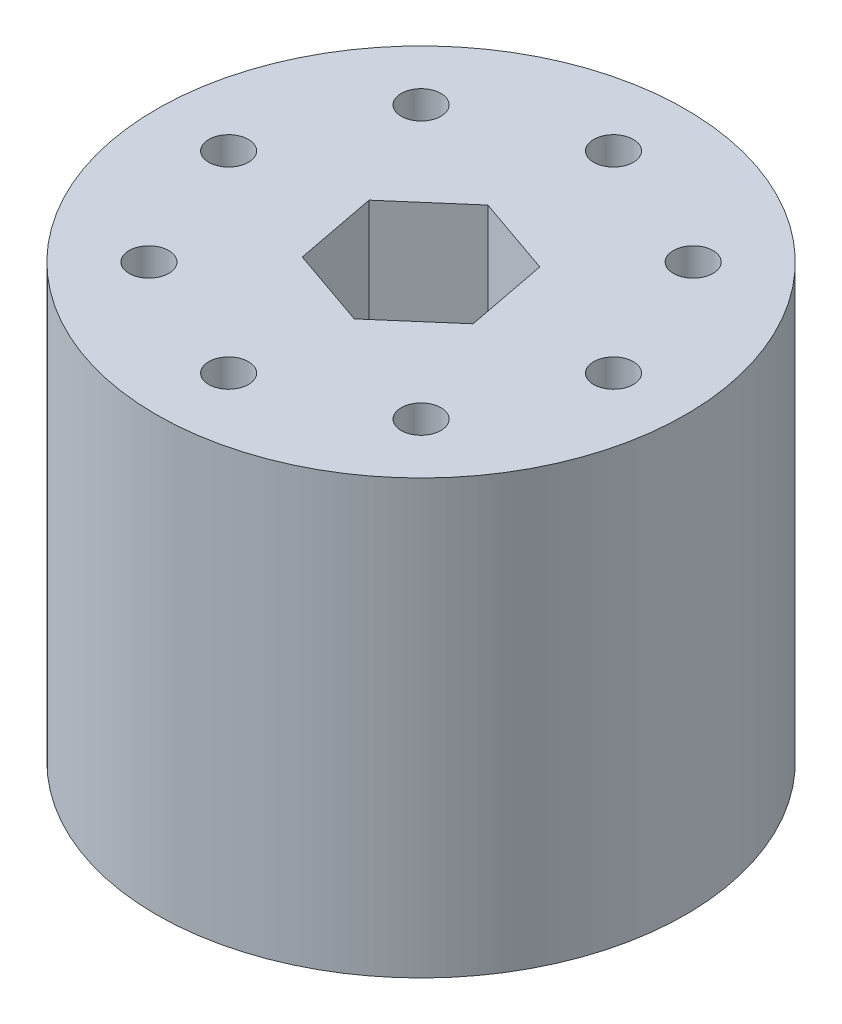
SolidWorks part; units mm, degrees
ref_plane "Front Plane" through (0, 0, 0) normal (0, 0, 1) x (1, 0, 0)
ref_plane "Top Plane" through (0, 0, 0) normal (0, 1, 0) x (1, 0, 0)
ref_plane "Right Plane" through (0, 0, 0) normal (1, 0, 0) x (0, 0, -1)
sketch "Sketch1" plane through (0, 0, 0) normal (0, 1, 0) x (1, 0, 0)
  circle A0 centre (0, 0) radius 22
extrude "Boss-Extrude1" add sketch "Sketch1" along normal blind 36
sketch "Sketch2" plane through (0, 36, 0) normal (0, 1, 0) x (1, 0, 0)
  line L0 (-11.3137, 11.3137) -> (11.3137, -11.3137) construction
  line L1 (11.3137, 11.3137) -> (-11.3137, -11.3137) construction
  line L2 (0, 16) -> (0, -16) construction
  line L3 (16, 0) -> (-16, 0) construction
  circle A3 centre (-11.3137, 11.3137) radius 1.65
  circle A4 centre (0, 16) radius 1.65
  circle A62 centre (16, 0) radius 1.65
  circle A63 centre (11.3137, 11.3137) radius 1.65
  circle A64 centre (0, -16) radius 1.65
  circle A65 centre (11.3137, -11.3137) radius 1.65
  circle A66 centre (-16, 0) radius 1.65
  circle A67 centre (-11.3137, -11.3137) radius 1.65
  circle A68 centre (-16, 0) radius 1.65 [skipped]
  circle A69 centre (-11.3137, -11.3137) radius 1.65 [skipped]
  circle A70 centre (0, -16) radius 1.65 [skipped]
  circle A71 centre (11.3137, -11.3137) radius 1.65 [skipped]
  circle A72 centre (16, 0) radius 1.65 [skipped]
  circle A73 centre (11.3137, 11.3137) radius 1.65 [skipped]
  point P25 (0, 0)
  point P43 (0, 0)
  point P172 (-1.004, 0.3293)
  dimension "D2" = 32
  dimension "D3" = 32
  dimension "D5" = 8
  dimension "D16" = 4
  dimension "D4" = 32
extrude "Cut-Extrude1" cut sketch "Sketch2" against normal up to vertex (36 mm away) up to point (0, 0, 0)
sketch "Sketch3" plane through (0, 36, 0) normal (0, 1, 0) x (1, 0, 0)
  line L1 (1.3217, -6.8741) -> (6.614, -2.2924)
  line L2 (6.614, -2.2924) -> (5.2923, 4.5817)
  line L3 (5.2923, 4.5817) -> (-1.3217, 6.8741)
  line L4 (-1.3217, 6.8741) -> (-6.614, 2.2924)
  line L5 (-6.614, 2.2924) -> (-5.2923, -4.5817)
  line L6 (-5.2923, -4.5817) -> (1.3217, -6.8741)
  circle A0 centre (0, 0) radius 6.0622 construction
  dimension "D1" = 7
extrude "Cut-Extrude2" cut sketch "Sketch3" against normal blind 10
sketch "Sketch4" plane through (0, 26, 0) normal (0, 1, 0) x (1, 0, 0)
  circle A0 centre (0, 0) radius 2.3
extrude "Cut-Extrude3" cut sketch "Sketch4" against normal blind 38
sketch "Sketch5" plane through (0, 0, 0) normal (0, -1, 0) x (-1, 0, 0)
  circle A0 centre (0, 0) radius 5.5954
extrude "Cut-Extrude4" cut sketch "Sketch5" against normal blind 9
